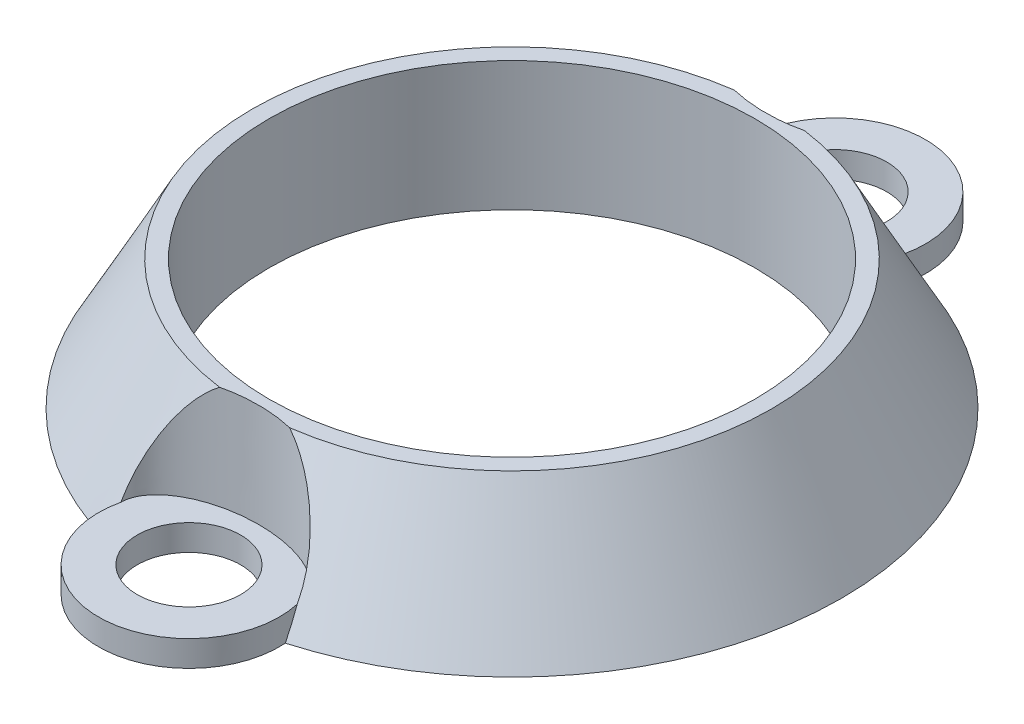
SolidWorks part; units mm, degrees
ref_plane "Plan de face" through (0, 0, 0) normal (0, 0, 1) x (1, 0, 0)
ref_plane "Plan de dessus" through (0, 0, 0) normal (0, 1, 0) x (1, 0, 0)
ref_plane "Plan de droite" through (0, 0, 0) normal (1, 0, 0) x (0, 0, -1)
sketch "Esquisse1" plane through (0, 0, 0) normal (0, 1, 0) x (1, 0, 0)
  arc A0 (-4.625, -8.0107) -> (4.625, -8.0107) centre (0, 0) ccw
  arc A3 (4.625, 8.0107) -> (-4.625, 8.0107) centre (0, 0) ccw
  arc A4 (-4.625, -8.0107) -> (-4.625, 8.0107) centre (0, 0) cw
  arc A5 (4.625, -8.0107) -> (4.625, 8.0107) centre (0, 0) ccw
  dimension "D1" = 18.5
extrude "Boss.-Extru.1" add sketch "Esquisse1" along normal blind 5 contours A0 A5 A3 A4
ref_axis "Axe1" through (0, 6.9782, 0) along (0, -1, 0)
sketch "Esquisse8" plane through (0, 0, 0) normal (0, 0, 1) x (1, 0, 0)
  line L1 (12.75, 0) -> (9.25, 0)
  line L2 (9.25, 0) -> (9.25, 5) construction
  line L3 (9.25, 0) -> (9.25, 5)
  line L4 (9.25, 5) -> (10.05, 5)
  line L5 (10.05, 5) -> (12.75, 0)
  dimension "D1" = 0.8
  dimension "D2" = 3.5
revolve "Révolution1" add sketch "Esquisse8" angle 360 about axis through (0, 6.9782, 0) along (0, -1, 0)
sketch "Esquisse12" plane through (0, 0, 0) normal (0, -1, 0) x (1, 0, 0)
  line L0 (0, -12.5) -> (0, 12.5) construction
  circle A0 centre (0, 12.5) radius 3.5
  circle A1 centre (0, -12.5) radius 3.5
  dimension "D2" = 7
  dimension "D1" = 25
extrude "Boss.-Extru.2" add sketch "Esquisse12" against normal blind 1
sketch "Esquisse10" plane through (0, 5, 0) normal (0, 1, 0) x (1, 0, 0)
  line L0 (-2.75, 0) -> (2.75, 0) construction
  circle A0 centre (0, 0) radius 10.05 construction
  ellipse E0 centre (0, 11.7234) end of major axis (3.4127, 11.7234) minor radius 1.9234
  ellipse E1 centre (0, -11.7234) end of major axis (3.4127, -11.7234) minor radius 1.9234
  point P18 (0, 0)
  point P20 (-12.2479, -10.2493)
  dimension "D1" = 9.8
extrude "Enlèv. mat.-Extru.5" cut sketch "Esquisse10" against normal up to surface (4 mm away) up to face at (0, 1, -14.105)
sketch "Esquisse13" plane through (0, 1, 0) normal (0, 1, 0) x (1, 0, 0)
  circle A0 centre (0, 12.5) radius 2
  circle A1 centre (0, -12.5) radius 2
  arc A2 (-3.4127, -11.7234) -> (3.4127, -11.7234) centre (0, -12.5) ccw construction
  arc A3 (3.4127, 11.7234) -> (-3.4127, 11.7234) centre (0, 12.5) ccw construction
  dimension "D1" = 4
extrude "Enlèv. mat.-Extru.7" cut sketch "Esquisse13" against normal through all
sketch "Esquisse11" plane through (0, 5, 0) normal (0, 1, 0) x (1, 0, 0)
  circle A0 centre (0, 0) radius 9.4
  dimension "D1" = 18.8
extrude "Enlèv. mat.-Extru.6" cut sketch "Esquisse11" against normal through all
